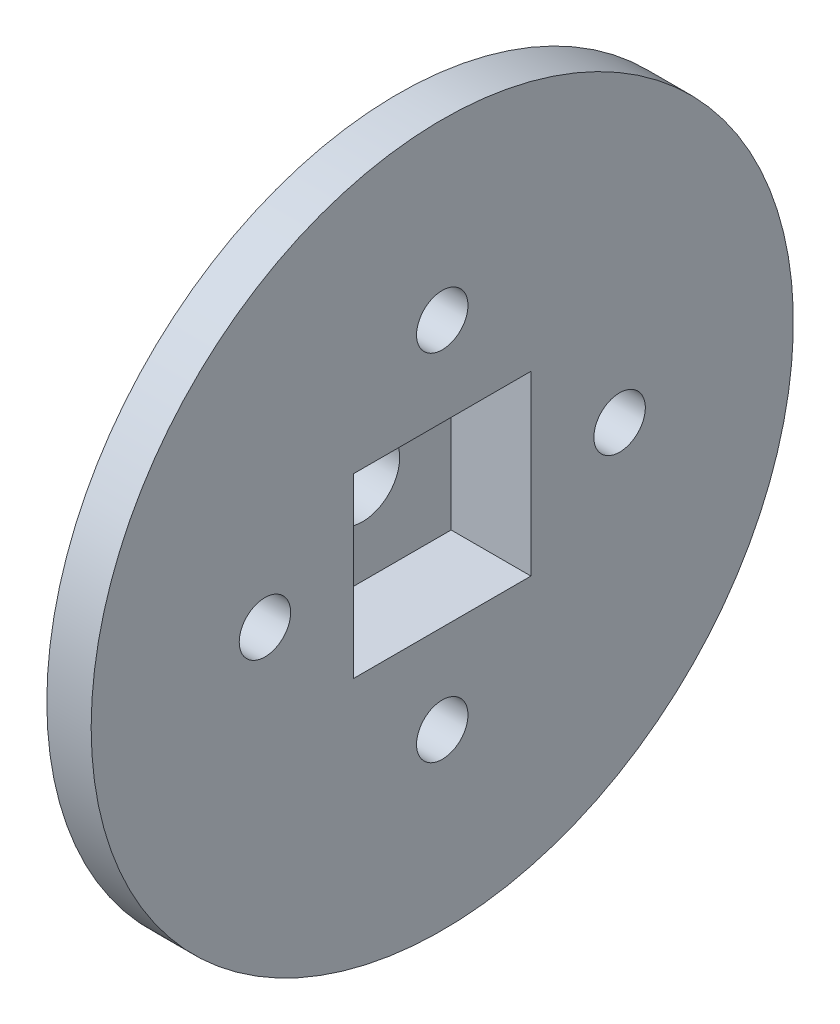
SolidWorks part; units mm, degrees
ref_plane "Plan de face" through (0, 0, 0) normal (0, 0, 1) x (1, 0, 0)
ref_plane "Plan de dessus" through (0, 0, 0) normal (0, 1, 0) x (1, 0, 0)
ref_plane "Plan de droite" through (0, 0, 0) normal (1, 0, 0) x (0, 0, -1)
sketch "Esquisse1" plane through (0, 0, 0) normal (0, 0, 1) x (1, 0, 0)
  line L0 (0, 0) -> (52.5351, 0) construction
  line L3 (0, 19.8) -> (0, 2.1)
  line L5 (-2.5, 8) -> (-2.5, 19.8)
  line L9 (0, 19.8) -> (-2.5, 19.8)
  line L10 (-2.5, 8) -> (-6, 8)
  line L11 (-6, 8) -> (-6, 2.1)
  line L13 (0, 2.1) -> (-6, 2.1)
  dimension "D1" = 2.5
  dimension "D2" = 3.5
  dimension "D3" = 8
  dimension "D4" = 4.2
  dimension "D5" = 39.6
revolve "Révolution1" add sketch "Esquisse1" angle 360 about L0
sketch "Esquisse2" plane through (-2.5, 0, 0) normal (-1, 0, 0) x (0, 0, 1)
  line L0 (0, 10) -> (0, -10) construction
  line L1 (10, 0) -> (-10, 0) construction
  circle A0 centre (0, 10) radius 1.45
  circle A1 centre (-10, 0) radius 1.45
  circle A2 centre (10, 0) radius 1.45
  circle A4 centre (0, 0) radius 10 construction
  circle A5 centre (0, -10) radius 1.45
  dimension "D2" = 2.9
  dimension "D3" = 20
extrude "Enlèv. mat.-Extru.1" cut sketch "Esquisse2" against normal through all
sketch "Esquisse3" plane through (0, 0, 0) normal (1, 0, 0) x (0, 0, -1)
  line L0 (0, 10) -> (0, 0) construction
  line L1 (3.6, 2.0785) -> (0, 4.1569) construction
  line L2 (0, 4.1569) -> (-3.6, 2.0785) construction
  line L3 (-3.6, 2.0785) -> (-3.6, -2.0785) construction
  line L4 (-3.6, -2.0785) -> (0, -4.1569) construction
  line L5 (0, -4.1569) -> (3.6, -2.0785) construction
  line L6 (3.6, -2.0785) -> (3.6, 2.0785) construction
  line L8 (-5, -5) -> (5, -5)
  line L9 (-5, -5) -> (-5, 5)
  line L10 (-5, 5) -> (5, 5)
  line L11 (5, -5) -> (5, 5)
  line L12 (-5, -5) -> (5, 5) construction
  line L13 (-5, 5) -> (5, -5) construction
  circle A0 centre (0, 0) radius 3.6 construction
  dimension "D1" = 7.2
  dimension "D2" = 10
extrude "Enlèv. mat.-Extru.2" cut sketch "Esquisse3" against normal blind 4.5
sketch "Esquisse4" plane through (-6, 0, 0) normal (-1, 0, 0) x (0, 0, 1)
  line L1 (-4, -4) -> (4, -4)
  line L2 (-4, -4) -> (-4, 4)
  line L3 (-4, 4) -> (4, 4)
  line L4 (4, -4) -> (4, 4)
  line L5 (-4, -4) -> (4, 4) construction
  line L6 (-4, 4) -> (4, -4) construction
  circle A0 centre (0, 0) radius 2.1 construction
  circle A1 centre (0, 0) radius 2.1
  point P0 (0, 0)
  dimension "D1" = 8
extrude "Boss.-Extru.1" add sketch "Esquisse4" along normal blind 4
sketch "Esquisse5" plane through (-2.5, 0, 0) normal (-1, 0, 0) x (0, 0, 1)
  circle A0 centre (0, 10) radius 3.45
  circle A1 centre (0, 10) radius 1.45 construction
  circle A2 centre (10, 0) radius 3.45
  circle A3 centre (0, -10) radius 3.45
  circle A4 centre (-10, 0) radius 3.45
  point P14 (0, 0)
  dimension "D1" = 2
  dimension "D2" = 4
extrude "Enlèv. mat.-Extru.3" cut sketch "Esquisse5" along normal through all
chamfer "Chanfrein1" distance 0.5 angle 45 4 edges at (-8, 4, -4) (-8, 4, 4) (-8, -4, -4) (-8, -4, 4)
sketch "Esquisse6" [suppressed] plane through (0, 0, 0) normal (1, 0, 0) x (0, 0, -1)
  line L1 (3.6, 2.0785) -> (0, 4.1569)
  line L2 (0, 4.1569) -> (-3.6, 2.0785)
  line L3 (-3.6, 2.0785) -> (-3.6, -2.0785)
  line L4 (-3.6, -2.0785) -> (0, -4.1569)
  line L5 (0, -4.1569) -> (3.6, -2.0785)
  line L6 (3.6, -2.0785) -> (3.6, 2.0785)
  circle A0 centre (0, 0) radius 3.6 construction
  dimension "D1" = 7.2
extrude "Enlèv. mat.-Extru.4" [suppressed] cut sketch "Esquisse6" against normal blind 4
